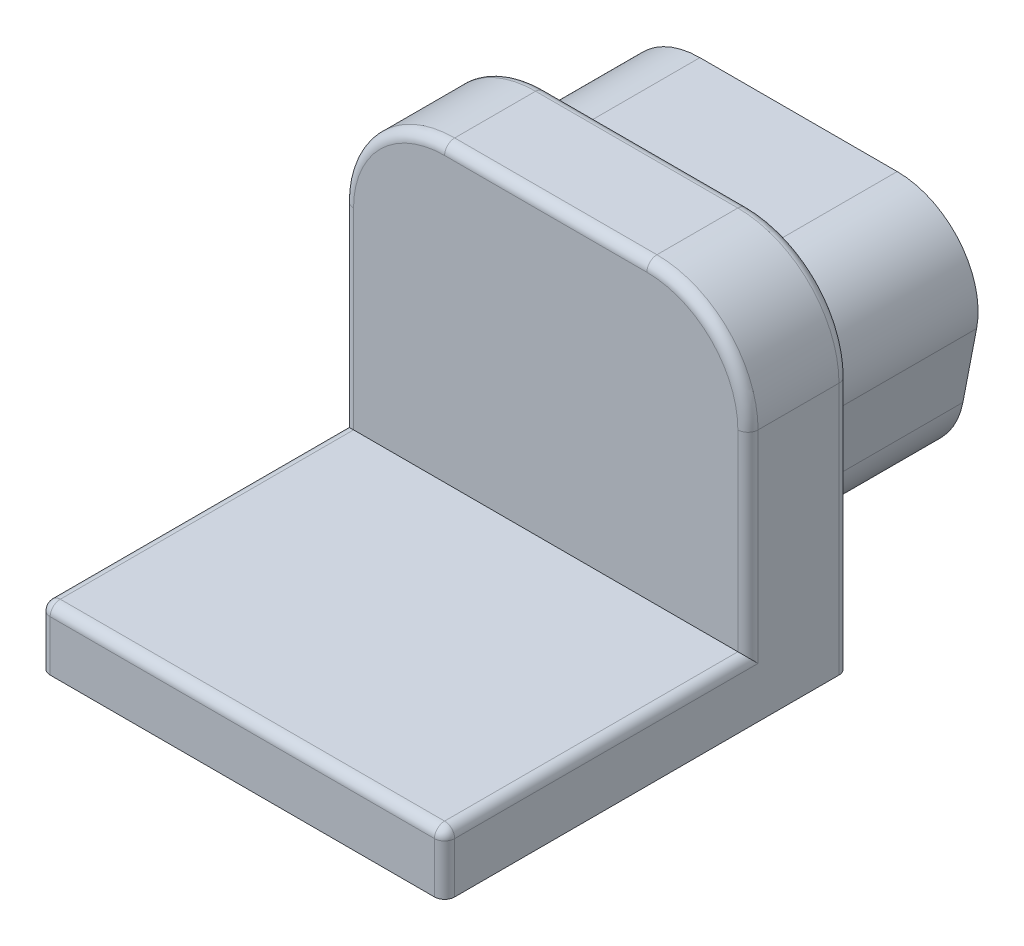
SolidWorks part; units mm, degrees
ref_plane "x/y" through (0, 0, 0) normal (0, 0, 1) x (1, 0, 0)
ref_plane "x/z" through (0, 0, 0) normal (0, 1, 0) x (1, 0, 0)
ref_plane "y/z" through (0, 0, 0) normal (1, 0, 0) x (0, 0, -1)
sketch "Sketch1" plane through (0, 0, 0) normal (0, 1, 0) x (1, 0, 0)
  line L1 (-10.16, -2.032) -> (0, -2.032)
  line L2 (-10.16, -2.032) -> (-10.16, 8.128)
  line L3 (-10.16, 8.128) -> (0, 8.128)
  line L4 (0, -2.032) -> (0, 8.128)
  point P3 (-5.08, 8.128)
  dimension "D1" = 10.16
  dimension "D2" = 10.16
  dimension "D3" = 2.032
  dimension "D4" = 10.16
extrude "Base-Extrude" add sketch "Sketch1" along normal blind 8.89
sketch "Sketch2" plane through (0, 0, -8.128) normal (0, 0, -1) x (-1, 0, 0)
  line L0 (5.08, 8.89) -> (5.08, -6.5379) construction
  line L1 (0, 8.89) -> (10.16, 8.89) construction
  line L2 (2.9465, 1.778) -> (7.2135, 1.778)
  line L3 (9.2085, 3.424) -> (9.5525, 5.202)
  line L4 (7.5575, 7.62) -> (2.6025, 7.62)
  line L6 (0.9515, 3.424) -> (0.6075, 5.202)
  line L7 (0, 0) -> (10.16, 0) construction
  arc A0 (9.2085, 3.424) -> (7.2135, 1.778) centre (7.2135, 3.81) cw
  arc A1 (7.5575, 7.62) -> (9.5525, 5.202) centre (7.5575, 5.588) cw
  arc A2 (2.6025, 7.62) -> (0.6075, 5.202) centre (2.6025, 5.588) ccw
  arc A3 (0.9515, 3.424) -> (2.9465, 1.778) centre (2.9465, 3.81) ccw
  point P4 (5.08, 7.62)
  point P12 (8.89, 1.778)
  point P21 (5.08, 1.778)
  dimension "D5" = 2.032
  dimension "D1" = 1.778
  dimension "D2" = 1.27
  dimension "D3" = 100.95
  dimension "D4" = 3.81
extrude "Boss-Extrude1" add sketch "Sketch2" along normal blind 3.81
sketch "Sketch4" plane through (0, 0, -11.938) normal (0, 0, -1) x (-1, 0, 0)
  line L0 (10.16, 8.89) -> (10.16, 0) construction
  line L2 (0, 8.89) -> (10.16, 8.89) construction
  circle A0 centre (7.874, 5.842) radius 0.635
  dimension "D1" = 1.27
  dimension "D2" = 2.286
  dimension "D3" = 3.048
extrude "Cut-Extrude1" cut sketch "Sketch4" against normal blind 5.08
sketch "Sketch5" plane through (0, 0, -11.938) normal (0, 0, -1) x (-1, 0, 0)
  line L0 (10.16, 8.89) -> (10.16, 0) construction
  line L2 (0, 0) -> (10.16, 0) construction
  circle A0 centre (6.477, 3.302) radius 0.635
  circle A1 centre (7.874, 5.842) radius 0.635 construction
  dimension "D2" = 3.302
  dimension "D1" = 3.683
extrude "Cut-Extrude2" cut sketch "Sketch5" against normal blind 5.08
sketch "Sketch6" plane through (0, 0, 0) normal (0, -1, 0) x (1, 0, 0)
  line L0 (-10.16, -8.128) -> (-10.16, 2.032) construction
  circle A0 centre (-5.08, 0) radius 0.3556
  dimension "D1" = 0.7112
  dimension "D2" = 5.08
extrude "Boss-Extrude2" add sketch "Sketch6" along normal blind 0.254
pattern_linear "LPattern1" count 2 spacing 2.7686 along (1, 0, 0) of "Boss-Extrude2"
pattern_linear "LPattern2" count 3 spacing 2.7686 along (1, 0, 0) of "Cut-Extrude1"
pattern_linear "LPattern3" count 2 spacing 2.7686 along (1, 0, 0) of "Cut-Extrude2"
sketch "Sketch7" plane through (0, 0, 0) normal (0, -1, 0) x (1, 0, 0)
  line L1 (-10.16, -8.128) -> (-10.16, 2.032) construction
  circle A0 centre (-5.08, -2.54) radius 0.3556
  dimension "D1" = 0.7112
  dimension "D2" = 5.08
  dimension "D3" = 2.54
extrude "Boss-Extrude3" add sketch "Sketch7" along normal up to surface (0.254 mm away) up to face at (-5.08, -0.254, -0.3556)
pattern_linear "LPattern4" count 2 spacing 2.7686 along (1, 0, 0) of "Boss-Extrude3"
ref_plane "Plane1" through (-5.08, 0, 0) normal (1, 0, 0) x (0, 0, -1)
fillet "Fillet1" radius 2.54 2 edges at (-10.16, 8.89, -3.048) (0, 8.89, -3.048)
fillet "Fillet2" radius 0.254 5 edges at (-5.08, 8.89, -8.128) (-10.16, 3.175, -8.128) (0, 3.175, -8.128) (-0.7439, 8.1461, -8.128) (-9.4161, 8.1461, -8.128)
fillet "Filete1" radius 0.254 5 edges at (-4.3434, 3.302, -11.938) (-7.112, 3.302, -11.938) (-8.509, 5.842, -11.938) (-5.7404, 5.842, -11.938) (-2.9718, 5.842, -11.938)
sketch "Sketch8" plane through (0, 8.89, 0) normal (0, 1, 0) x (1, 0, 0)
  line L0 (-7.5575, 8.128) -> (-2.6025, 8.128) construction
  line L1 (-12.5846, 5.588) -> (5.2309, 5.588)
  line L2 (-12.5846, 5.588) -> (-12.5846, -2.3478)
  line L3 (-12.5846, -2.3478) -> (5.2309, -2.3478)
  line L4 (5.2309, 5.588) -> (5.2309, -2.3478)
  dimension "D1" = 2.54
extrude "Cut-Extrude3" cut sketch "Sketch8" against normal blind 7.366
fillet "Fillet3" radius 0.254 10 edges at (0, 0.762, 2.032) (-10.16, 0.762, 2.032) (-5.08, 1.524, 2.032) (0, 1.524, -1.778) (0, 3.937, -5.588) (-0.7439, 8.1461, -5.588) (-5.08, 8.89, -5.588) (-9.4161, 8.1461, -5.588) (-10.16, 3.937, -5.588) (-10.16, 1.524, -1.778)
